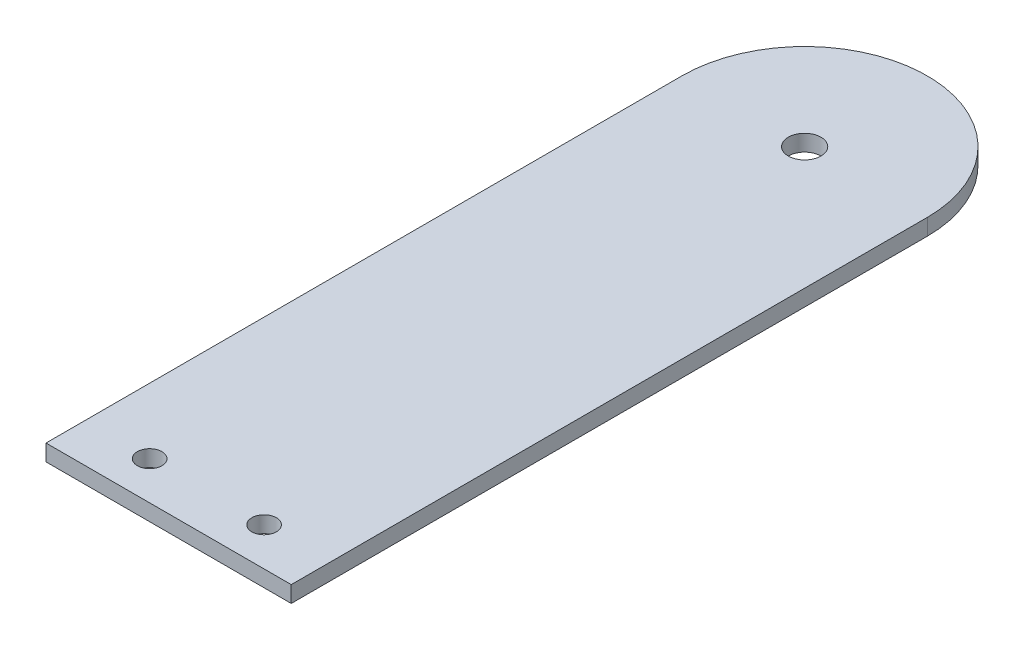
SolidWorks part; units mm, degrees
ref_plane "Спереди" through (0, 0, 0) normal (0, 0, 1) x (1, 0, 0)
ref_plane "Сверху" through (0, 0, 0) normal (0, 1, 0) x (1, 0, 0)
ref_plane "Справа" through (0, 0, 0) normal (1, 0, 0) x (0, 0, -1)
sketch "Эскиз1" plane through (0, 0, 0) normal (0, 1, 0) x (1, 0, 0)
  line L0 (-17.6252, -24.9379) -> (12.3748, -24.9379) construction
  line L1 (-17.6252, -29.6173) -> (12.3748, -29.6173)
  line L2 (-17.6252, -29.6173) -> (-17.6252, 48.1827)
  line L3 (-17.6252, 52.3827) -> (12.3748, 52.3827) construction
  line L4 (12.3748, -29.6173) -> (12.3748, 48.1827)
  line L5 (-9.6252, -26.4379) -> (4.3748, -26.4379) construction
  line L6 (-2.6252, -29.6173) -> (-2.6252, 60.301) construction
  circle A0 centre (-9.6252, -24.9379) radius 1.5
  circle A1 centre (4.3748, -24.9379) radius 1.5
  circle A2 centre (-2.6252, 48.1827) radius 2
  arc A4 (12.3748, 48.1827) -> (-17.6252, 48.1827) centre (-2.6252, 48.1827) ccw
  dimension "D3" = 77.8
  dimension "D4" = 4
  dimension "D7" = 3
  dimension "D2" = 30
  dimension "D5" = 14
  dimension "D6" = 8
extrude "Бобышка-Вытянуть1" add sketch "Эскиз1" along normal blind 2
